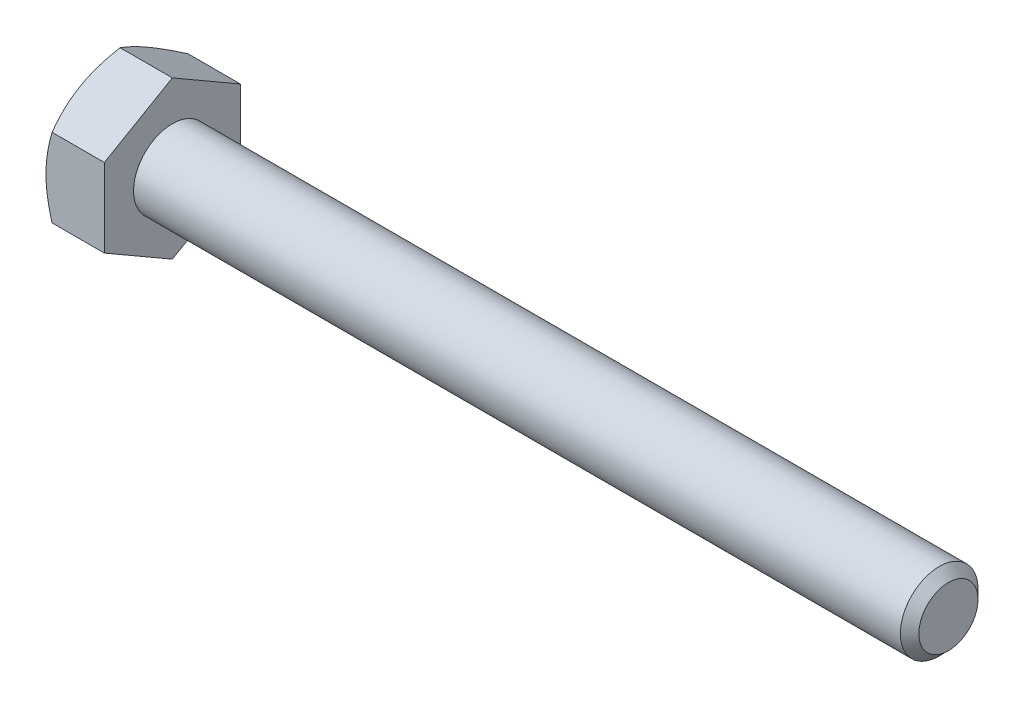
SolidWorks part; units mm, degrees
ref_plane "Plane1" through (0, 0, 0) normal (0, 0, 1) x (1, 0, 0)
ref_plane "Plane2" through (0, 0, 0) normal (0, 1, 0) x (1, 0, 0)
ref_plane "Plane3" through (0, 0, 0) normal (1, 0, 0) x (0, 0, -1)
sketch "Sketch1" plane through (0, 0, 0) normal (1, 0, 0) x (0, 0, -1)
  line L0 (5.5626, 3.2116) -> (5.5626, -3.2116)
  line L1 (-5.5626, 3.2116) -> (-5.5626, -3.2116)
  line L2 (5.5626, -3.2116) -> (0, -6.4231)
  line L3 (0, -6.4231) -> (-5.5626, -3.2116)
  line L4 (5.5626, 3.2116) -> (0, 6.4231)
  line L5 (0, 6.4231) -> (-5.5626, 3.2116)
  dimension "Width_flats" = 11.1252
  dimension "D2" = 120
  dimension "D3" = 5.5626
  dimension "D4" = 5.5626
  dimension "D5" = 5.5626
extrude "BaseHead" add sketch "Sketch1" along normal blind 4.7752
sketch "BodySke" plane through (0, 0, 0) normal (0, 0, 1) x (1, 0, 0)
  line L0 (0, 3.2116) -> (0, -3.2116) construction
  line L1 (0, 0) -> (68.2752, 0)
  line L2 (0, 0) -> (0, 3.175)
  line L3 (0, 3.175) -> (67.5195, 3.175)
  line L4 (68.2752, 0) -> (68.2752, 2.4193)
  line L5 (4.7752, 6.4231) -> (4.7752, 3.2116) construction
  line L6 (68.2752, 2.4193) -> (67.5195, 3.175)
  line L7 (0, 0) -> (96.52, 0) construction
  line L8 (68.2752, -2.4193) -> (67.5195, -3.175) construction
  line L9 (0, -3.175) -> (67.5195, -3.175) construction
  line L10 (6.0452, 15.24) -> (6.0452, -2.54) construction
  line L11 (49.2252, 15.24) -> (49.2252, -2.54) construction
  line L12 (4.7752, 3.2116) -> (4.7752, -3.2116) construction
  dimension "Length" = 63.5
  dimension "Body_ch_ang" = 45
  dimension "Diameter" = 6.35
  dimension "Minor_dia" = 4.8387
  dimension "Advance" = 1.27
  dimension "Thread_nom" = 19.05
revolve "BaseBody" add sketch "BodySke" angle 360 about L7
cosmetic thread "ThreadCosmetic" [suppressed] parameters "Thread_length"=19.05, "Thread_minor"=4.8387
sketch "Sketch3" plane through (0, 0, 0) normal (0, 0, 1) x (1, 0, 0)
  line L0 (0, 5.5626) -> (4.163, 12.7731)
  line L1 (0, 6.4231) -> (0, 3.2116) construction
  line L2 (4.163, 12.7731) -> (4.163, 19.1231)
  line L3 (4.163, 19.1231) -> (-12.7, 19.1231)
  line L4 (-12.7, 19.1231) -> (-12.7, 5.5626)
  line L5 (-12.7, 5.5626) -> (0, 5.5626)
  line L6 (0, 0) -> (99.06, 0) construction
  line L7 (4.7752, 6.4231) -> (0, 6.4231) construction
  dimension "D1" = 5.5626
  dimension "D2" = 6.35
  dimension "D3" = 12.7
  dimension "D4" = 6.35
  dimension "Head_ch_ang" = 30
revolve "HeadChamfer" cut sketch "Sketch3" angle 360 about L6
fillet "HeadFillet" [suppressed] radius 0.762
sketch "ThdSchSke" plane through (0, 0, 0) normal (0, 0, 1) x (1, 0, 0)
  line L0 (49.2252, -2.4193) -> (48.6961, -3.175)
  line L1 (49.2252, -2.4193) -> (49.7543, -3.175)
  line L2 (49.7543, -3.175) -> (49.7543, -3.9687)
  line L3 (-3.175, 0) -> (5.1513, 0) construction
  line L5 (49.7543, -3.9687) -> (48.6961, -3.9687)
  line L6 (48.6961, -3.9687) -> (48.6961, -3.175)
  dimension "Thread_minor" = 4.8387
  dimension "Diameter" = 6.35
  dimension "Start" = 49.2252
  dimension "SideAngle" = 55
  dimension "VeeAngle" = 70
  dimension "Overcut" = 7.9375
revolve "ThreadSchematic" [suppressed] cut sketch "ThdSchSke" angle 360 about L3
pattern_linear "ThdSchPat" [suppressed]
equation "\"D3@Sketch1\" = \"Width_flats@Sketch1\" / 2"
equation "\"D4@Sketch1\" = \"D3@Sketch1\""
equation "\"D5@Sketch1\" = \"D4@Sketch1\""
equation "\"Thread_minor@ThreadCosmetic\" = \"Minor_dia@BodySke\""
equation "\"D1@Sketch3\" = \"Width_flats@Sketch1\" / 2"
equation "\"Thread_length@ThreadCosmetic\" = ((sgn( (\"Length@BodySke\" - \"Advance@BodySke\" ) - \"Thread_nom@BodySke\" )-1)*( (\"Length@BodySke\" - \"Advance@BodySke\" ) - \"Thread_nom@BodySke\" ))/-2+ \"Thread_nom@BodySke\""
equation "\"Thread_minor@ThdSchSke\" = \"Minor_dia@BodySke\""
equation "\"Diameter@ThdSchSke\" = \"Diameter@BodySke\""
equation "\"Overcut@ThdSchSke\" = \"Diameter@BodySke\" * 1.25"
equation "\"Start@ThdSchSke\" = \"Head_ht@BaseHead\" + \"Length@BodySke\" - \"Thread_length@ThreadCosmetic\"  '---Non-countersunk---"
equation "\"Num_threads@ThdSchPat\" = int( \"Thread_length@ThreadCosmetic\" / \"Advance@BodySke\" + 0.999 )  + 1"
equation "\"Advance@ThdSchPat\" = \"Thread_length@ThreadCosmetic\" /  (\"Num_threads@ThdSchPat\" - 1) 'relax it"
equation "\"Num_threads@ThdSchPat\" = \"Num_threads@ThdSchPat\" - sgn( \"Num_threads@ThdSchPat\" - 1) '---chamfered tips only---"
